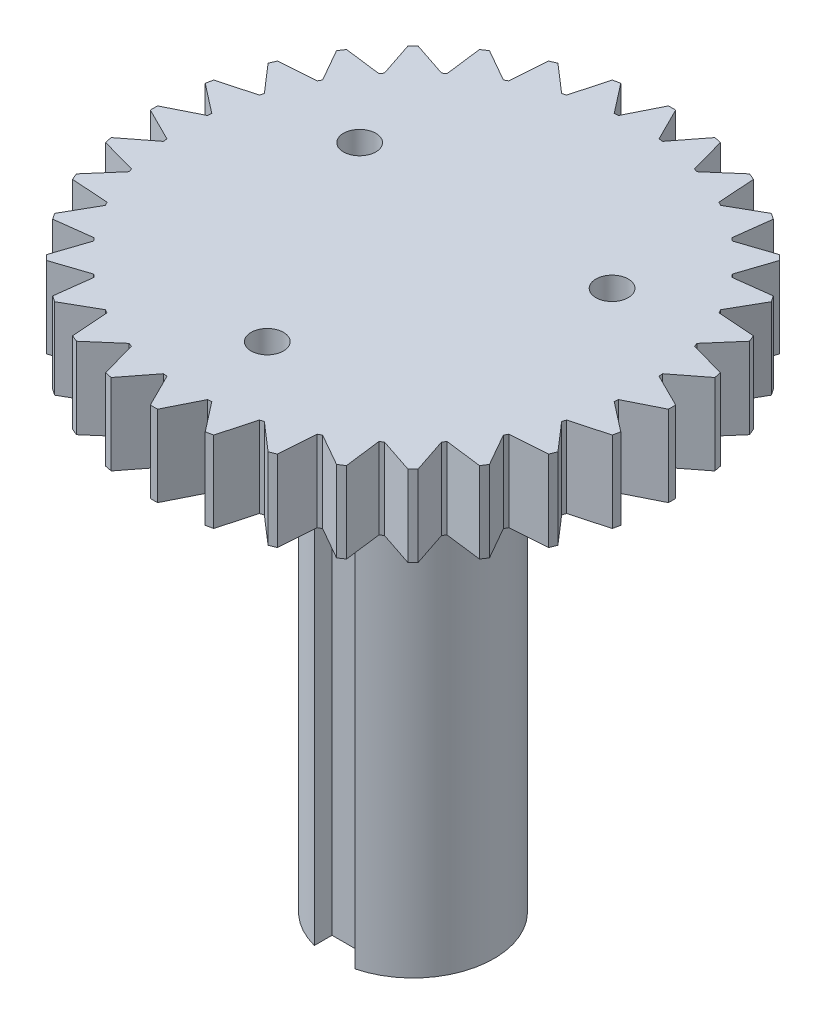
SolidWorks part; units mm, degrees
ref_plane "Front Plane" through (0, 0, 0) normal (0, 0, 1) x (1, 0, 0)
ref_plane "Top Plane" through (0, 0, 0) normal (0, 1, 0) x (1, 0, 0)
ref_plane "Right Plane" through (0, 0, 0) normal (1, 0, 0) x (0, 0, -1)
sketch "Sketch1" plane through (0, 0, 0) normal (0, 1, 0) x (1, 0, 0)
  line L0 (0, 17.709) -> (0, 17.78) construction
  line L1 (0, 20.884) -> (1.5875, 17.709)
  line L2 (0, 20.884) -> (-1.5875, 17.709)
  line L4 (4.0743, 20.4827) -> (1.8979, 17.6784)
  line L5 (4.0743, 20.4827) -> (5.0118, 17.059)
  line L6 (7.992, 19.2943) -> (5.3103, 16.9685)
  line L7 (7.992, 19.2943) -> (8.2436, 15.7535)
  line L8 (11.6025, 17.3644) -> (8.5186, 15.6065)
  line L9 (11.6025, 17.3644) -> (11.1585, 13.8425)
  line L10 (14.7672, 14.7672) -> (11.3996, 13.6447)
  line L11 (14.7672, 14.7672) -> (13.6447, 11.3996)
  line L12 (17.3644, 11.6025) -> (13.8425, 11.1585)
  line L13 (17.3644, 11.6025) -> (15.6065, 8.5186)
  line L14 (19.2943, 7.992) -> (15.7535, 8.2436)
  line L15 (19.2943, 7.992) -> (16.9685, 5.3103)
  line L16 (20.4827, 4.0743) -> (17.059, 5.0118)
  line L17 (20.4827, 4.0743) -> (17.6784, 1.8979)
  line L18 (20.884, 0) -> (17.709, 1.5875)
  line L19 (20.884, 0) -> (17.709, -1.5875)
  line L20 (20.4827, -4.0743) -> (17.6784, -1.8979)
  line L21 (20.4827, -4.0743) -> (17.059, -5.0118)
  line L22 (19.2943, -7.992) -> (16.9685, -5.3103)
  line L23 (19.2943, -7.992) -> (15.7535, -8.2436)
  line L24 (17.3644, -11.6025) -> (15.6065, -8.5186)
  line L25 (17.3644, -11.6025) -> (13.8425, -11.1585)
  line L26 (14.7672, -14.7672) -> (13.6447, -11.3996)
  line L27 (14.7672, -14.7672) -> (11.3996, -13.6447)
  line L28 (11.6025, -17.3644) -> (11.1585, -13.8425)
  line L29 (11.6025, -17.3644) -> (8.5186, -15.6065)
  line L30 (7.992, -19.2943) -> (8.2436, -15.7535)
  line L31 (7.992, -19.2943) -> (5.3103, -16.9685)
  line L32 (4.0743, -20.4827) -> (5.0118, -17.059)
  line L33 (4.0743, -20.4827) -> (1.8979, -17.6784)
  line L34 (0, -20.884) -> (1.5875, -17.709)
  line L35 (0, -20.884) -> (-1.5875, -17.709)
  line L36 (-4.0743, -20.4827) -> (-1.8979, -17.6784)
  line L37 (-4.0743, -20.4827) -> (-5.0118, -17.059)
  line L38 (-7.992, -19.2943) -> (-5.3103, -16.9685)
  line L39 (-7.992, -19.2943) -> (-8.2436, -15.7535)
  line L40 (-11.6025, -17.3644) -> (-8.5186, -15.6065)
  line L41 (-11.6025, -17.3644) -> (-11.1585, -13.8425)
  line L42 (-14.7672, -14.7672) -> (-11.3996, -13.6447)
  line L43 (-14.7672, -14.7672) -> (-13.6447, -11.3996)
  line L44 (-17.3644, -11.6025) -> (-13.8425, -11.1585)
  line L45 (-17.3644, -11.6025) -> (-15.6065, -8.5186)
  line L46 (-19.2943, -7.992) -> (-15.7535, -8.2436)
  line L47 (-19.2943, -7.992) -> (-16.9685, -5.3103)
  line L48 (-20.4827, -4.0743) -> (-17.059, -5.0118)
  line L49 (-20.4827, -4.0743) -> (-17.6784, -1.8979)
  line L50 (-20.884, 0) -> (-17.709, -1.5875)
  line L51 (-20.884, 0) -> (-17.709, 1.5875)
  line L52 (-20.4827, 4.0743) -> (-17.6784, 1.8979)
  line L53 (-20.4827, 4.0743) -> (-17.059, 5.0118)
  line L54 (-19.2943, 7.992) -> (-16.9685, 5.3103)
  line L55 (-19.2943, 7.992) -> (-15.7535, 8.2436)
  line L56 (-17.3644, 11.6025) -> (-15.6065, 8.5186)
  line L57 (-17.3644, 11.6025) -> (-13.8425, 11.1585)
  line L58 (-14.7672, 14.7672) -> (-13.6447, 11.3996)
  line L59 (-14.7672, 14.7672) -> (-11.3996, 13.6447)
  line L60 (-11.6025, 17.3644) -> (-11.1585, 13.8425)
  line L61 (-11.6025, 17.3644) -> (-8.5186, 15.6065)
  line L62 (-7.992, 19.2943) -> (-8.2436, 15.7535)
  line L63 (-7.992, 19.2943) -> (-5.3103, 16.9685)
  line L64 (-4.0743, 20.4827) -> (-5.0118, 17.059)
  line L65 (-4.0743, 20.4827) -> (-1.8979, 17.6784)
  arc A0 (-1.5875, 17.709) -> (-1.8979, 17.6784) centre (0, 0) ccw
  arc A1 (-5.0118, 17.059) -> (-5.3103, 16.9685) centre (0, 0) ccw
  arc A2 (-8.2436, 15.7535) -> (-8.5186, 15.6065) centre (0, 0) ccw
  arc A3 (-11.1585, 13.8425) -> (-11.3996, 13.6447) centre (0, 0) ccw
  arc A4 (-13.6447, 11.3996) -> (-13.8425, 11.1585) centre (0, 0) ccw
  arc A5 (-15.6065, 8.5186) -> (-15.7535, 8.2436) centre (0, 0) ccw
  arc A6 (-16.9685, 5.3103) -> (-17.059, 5.0118) centre (0, 0) ccw
  arc A7 (-17.6784, 1.8979) -> (-17.709, 1.5875) centre (0, 0) ccw
  arc A8 (-17.709, -1.5875) -> (-17.6784, -1.8979) centre (0, 0) ccw
  arc A9 (-17.059, -5.0118) -> (-16.9685, -5.3103) centre (0, 0) ccw
  arc A10 (-15.7535, -8.2436) -> (-15.6065, -8.5186) centre (0, 0) ccw
  arc A11 (-13.8425, -11.1585) -> (-13.6447, -11.3996) centre (0, 0) ccw
  arc A12 (-11.3996, -13.6447) -> (-11.1585, -13.8425) centre (0, 0) ccw
  arc A13 (-8.5186, -15.6065) -> (-8.2436, -15.7535) centre (0, 0) ccw
  arc A14 (-5.3103, -16.9685) -> (-5.0118, -17.059) centre (0, 0) ccw
  arc A15 (-1.8979, -17.6784) -> (-1.5875, -17.709) centre (0, 0) ccw
  arc A16 (1.5875, -17.709) -> (1.8979, -17.6784) centre (0, 0) ccw
  arc A17 (5.0118, -17.059) -> (5.3103, -16.9685) centre (0, 0) ccw
  arc A18 (8.2436, -15.7535) -> (8.5186, -15.6065) centre (0, 0) ccw
  arc A19 (11.1585, -13.8425) -> (11.3996, -13.6447) centre (0, 0) ccw
  arc A20 (13.6447, -11.3996) -> (13.8425, -11.1585) centre (0, 0) ccw
  arc A21 (15.6065, -8.5186) -> (15.7535, -8.2436) centre (0, 0) ccw
  arc A22 (17.6784, -1.8979) -> (17.709, -1.5875) centre (0, 0) ccw
  arc A23 (16.9685, -5.3103) -> (17.059, -5.0118) centre (0, 0) ccw
  arc A24 (17.709, 1.5875) -> (17.6784, 1.8979) centre (0, 0) ccw
  arc A25 (17.059, 5.0118) -> (16.9685, 5.3103) centre (0, 0) ccw
  arc A26 (15.7535, 8.2436) -> (15.6065, 8.5186) centre (0, 0) ccw
  arc A27 (13.8425, 11.1585) -> (13.6447, 11.3996) centre (0, 0) ccw
  arc A28 (11.3996, 13.6447) -> (11.1585, 13.8425) centre (0, 0) ccw
  arc A29 (8.5186, 15.6065) -> (8.2436, 15.7535) centre (0, 0) ccw
  arc A30 (5.3103, 16.9685) -> (5.0118, 17.059) centre (0, 0) ccw
  arc A31 (1.8979, 17.6784) -> (1.5875, 17.709) centre (0, 0) ccw
  dimension "D1" = 35.56
  dimension "D2" = 3.175
  dimension "D3" = 3.175
  dimension "D4" = 32
extrude "Boss-Extrude1" add sketch "Sketch1" along normal blind 6.35
sketch "Sketch2" plane through (0, 6.35, 0) normal (0, 1, 0) x (-1, 0, 0)
  circle A0 centre (0, 0) radius 20.32
  dimension "D1" = 40.64
extrude "Cut-Extrude1" cut sketch "Sketch2" against normal through all flip side to cut
sketch "Sketch3" plane through (0, 0, 0) normal (0, -1, 0) x (1, 0, 0)
  line L0 (0, 0) -> (0, 4.7625) construction
  line L2 (-1.5875, 4.7625) -> (1.5875, 4.7625)
  line L3 (-1.5875, 4.7625) -> (-1.5875, 6.1484)
  line L5 (1.5875, 4.7625) -> (1.5875, 6.1484)
  arc A0 (-1.5875, 6.1484) -> (1.5875, 6.1484) centre (0, 0) ccw
  dimension "D2" = 12.7
extrude "Boss-Extrude2" add sketch "Sketch3" along normal blind 38.1
sketch "Sketch4" plane through (0, 0, 0) normal (0, -1, 0) x (1, 0, 0)
  line L0 (0, 0) -> (0, 11.43) construction
  line L2 (3.6662, 11.43) -> (1.8331, 14.605)
  line L3 (1.8331, 14.605) -> (-1.8331, 14.605)
  line L4 (-1.8331, 14.605) -> (-3.6662, 11.43)
  line L5 (-3.6662, 11.43) -> (-1.8331, 8.255)
  line L6 (-1.8331, 8.255) -> (1.8331, 8.255)
  line L7 (1.8331, 8.255) -> (3.6662, 11.43)
  circle A0 centre (0, 11.43) radius 3.175 construction
  dimension "D1" = 11.43
  dimension "D3" = 6.35
extrude "Cut-Extrude3" cut sketch "Sketch4" against normal blind 2.54
sketch "Sketch7" plane through (0, 2.54, 0) normal (0, -1, 0) x (1, 0, 0)
  line L0 (3.6662, 11.43) -> (-3.6662, 11.43) construction
  circle A0 centre (0, 11.43) radius 1.27
  dimension "D1" = 2.54
extrude "Cut-Extrude4" cut sketch "Sketch7" against normal through all
pattern_circular "CirPattern2" count 3 over 360 about axis through (0, 0, 0) along (0, 1, 0) of "Cut-Extrude3", "Cut-Extrude4"
